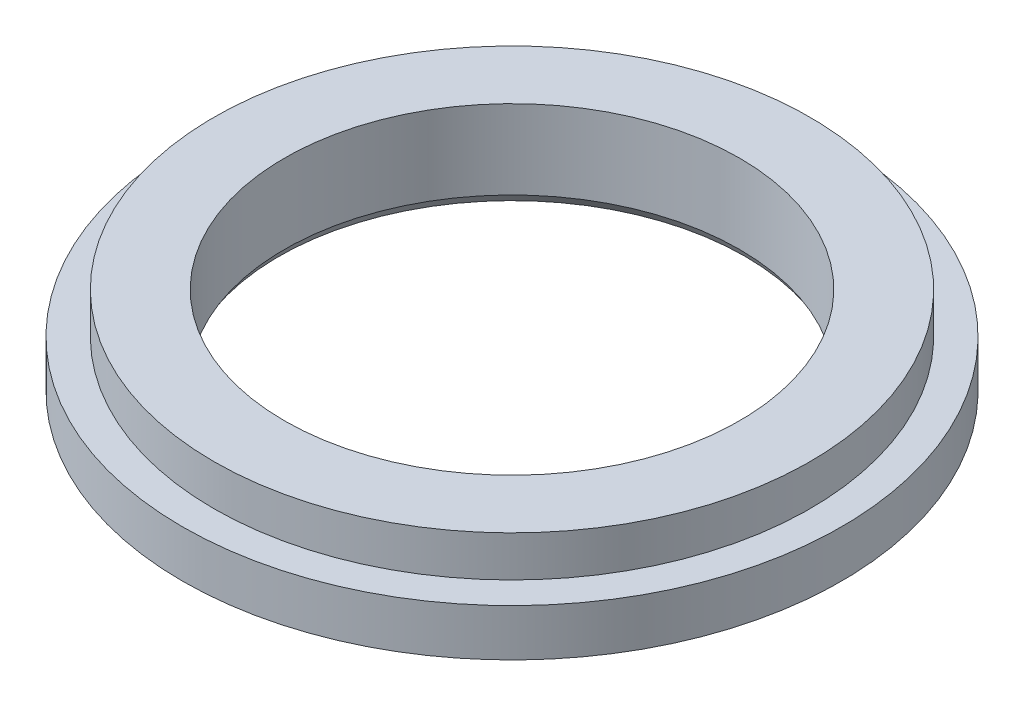
SolidWorks part; units mm, degrees
material "6061-T6 (SS)"
ref_plane "Front Plane" through (0, 0, 0) normal (0, 0, 1) x (1, 0, 0)
ref_plane "Top Plane" through (0, 0, 0) normal (0, 1, 0) x (1, 0, 0)
ref_plane "Right Plane" through (0, 0, 0) normal (1, 0, 0) x (0, 0, -1)
sketch "Sketch2" plane through (0, 0, 0) normal (0, 0, 1) x (1, 0, 0)
  line L0 (0, 0) -> (0, -50000) construction
  line L1 (-46.0375, 0) -> (-66.675, 0)
  line L2 (-66.675, 0) -> (-66.675, 9.525)
  line L3 (-66.675, 9.525) -> (-60.325, 9.525)
  line L4 (-60.325, 9.525) -> (-60.325, 17.78)
  line L5 (-60.325, 17.78) -> (-46.0375, 17.78)
  line L6 (-46.0375, 17.78) -> (-46.0375, 0)
  dimension "D1" = 92.075
  dimension "D2" = 133.35
  dimension "D3" = 120.65
  dimension "D4" = 17.78
  dimension "D5" = 9.525
revolve "Revolve1" add sketch "Sketch2" angle 360 about L0
chamfer "Chamfer1" distance 1.778 angle 32 1 edges at (0, 0, 46.0375)
hole_wizard "M4x0.7 Tapped Hole2" positions "Sketch6" profile "Sketch5" tap size "M4x0.7" standard "Ansi Metric"
sketch "Sketch6" plane through (0, 0, 0) normal (0, -1, 0) x (1, 0, 0)
  point P0 (0, 53.34)
  dimension "D1" = 53.34
sketch "Sketch5" plane through (0, 0, 53.34) normal (1, 0, 0) x (0, 0, -1)
  line L0 (0, 0) -> (0, 12.617)
  line L1 (0, 12.617) -> (1.65, 11.6256)
  line L2 (1.65, 11.6256) -> (1.65, 0)
  line L5 (1.65, 0) -> (0, 0)
  line L10 (0, 12.617) -> (-1.65, 11.6256) construction
  line L11 (0, -6.35) -> (0, 107.95) construction
  dimension "Tap Drill Dia." = 3.3
  dimension "Tap Drill Depth" = 11.6256
  dimension "Drill Angle" = 118
pattern_circular "CirPattern1" count 4 over 360 about axis through (0, 0, 0) along (0, 1, 0) of "M4x0.7 Tapped Hole2"
